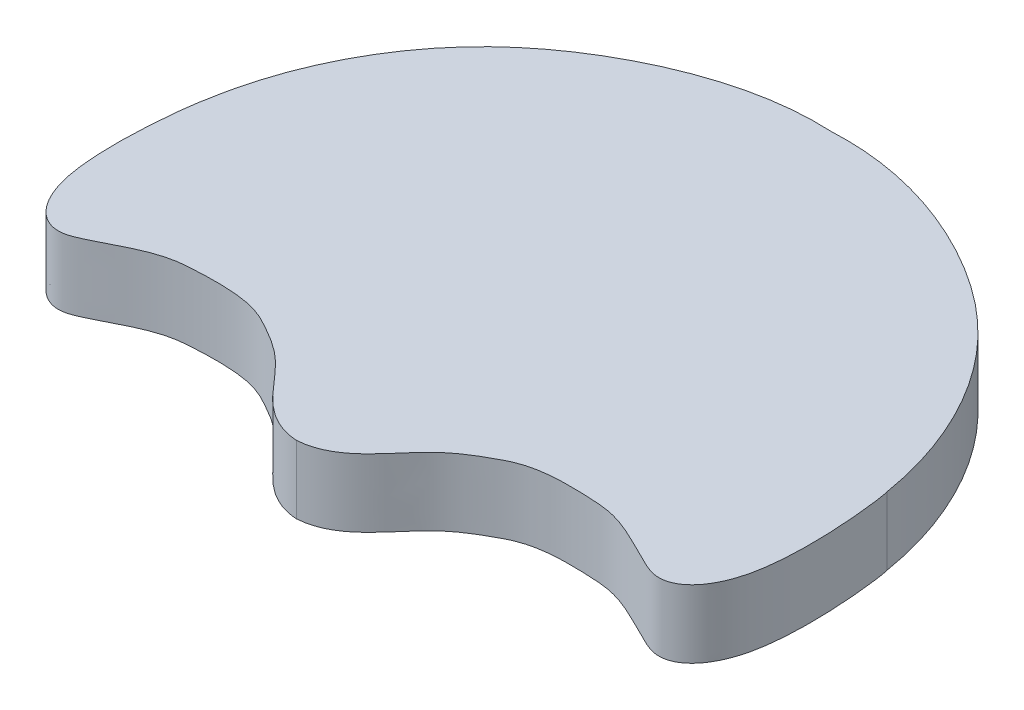
SolidWorks part; units mm, degrees
material "6061-T6 (SS)"
ref_plane "Front Plane" through (0, 0, 0) normal (0, 0, 1) x (1, 0, 0)
ref_plane "Top Plane" through (0, 0, 0) normal (0, 1, 0) x (1, 0, 0)
ref_plane "Right Plane" through (0, 0, 0) normal (1, 0, 0) x (0, 0, -1)
sketch "Sketch3" plane through (0, 0, 0) normal (0, 1, 0) x (1, 0, 0)
  line L0 (0, 0) -> (0, 159.1899) construction
  line L1 (0, 0) -> (0, -140.5301) construction
  line L2 (0, 0) -> (-190.5, 0) construction
  line L3 (0, 0) -> (190.5, 0) construction
  spline S0 degree 3 poles (-190.5, 0) (-184.3927, 37.537) (-157.2613, 93.9641) (-82.3875, 146.6227) (-31.3114, 160.7999) (0, 159.1899) knots 0 0 0 0 0.424401 0.65637 1 1 1 1
  spline S1 degree 3 poles (-190.5, 0) (-192.064, -4.9635) (-201.9672, -83.3146) (-174.6966, -109.29) (-151.6301, -100.568) (-131.4108, -87.7198) (-96.8436, -85.3754) (-78.6925, -86.2588) (-58.8335, -96.8794) (-37.3059, -109.9358) (-21.3496, -139.1148) (0, -140.5301) knots 0 0 0 0 0.166997 0.292321 0.319633 0.426735 0.458914 0.609242 0.64191 0.766802 1 1 1 1
  spline S2 degree 3 poles (190.5, 0) (192.064, -4.9635) (201.9672, -83.3146) (174.6966, -109.29) (151.6301, -100.568) (131.4108, -87.7198) (96.8436, -85.3754) (78.6925, -86.2588) (58.8335, -96.8794) (37.3059, -109.9358) (21.3496, -139.1148) (0, -140.5301) knots 0 0 0 0 0.166997 0.292321 0.319633 0.426735 0.458914 0.609242 0.64191 0.766802 1 1 1 1
  spline S3 degree 3 poles (190.5, 0) (184.3927, 37.537) (157.2613, 93.9641) (82.3875, 146.6227) (31.3114, 160.7999) (0, 159.1899) knots 0 0 0 0 0.424401 0.65637 1 1 1 1
  dimension "D1" = 381
  dimension "D2" = 299.72
  dimension "D3" = 159.1899
  dimension "D4" = 86.8953
  dimension "D5" = 104.4979
  dimension "D6" = 29.1616
  dimension "D7" = 92.2742
  dimension "D8" = 108.411
  dimension "D9" = 67.4883
  dimension "D10" = 43.7314
  dimension "D11" = 117.6915
  dimension "D12" = 162.2568
  dimension "D13" = 89.4522
  dimension "D14" = 140.1036
  dimension "D15" = 175.0666
  dimension "D16" = 50.2669
  dimension "D17" = 101.3666
  dimension "D18" = 138.1225
  dimension "D19" = 155.1557
  dimension "D20" = 192.0074
  dimension "D21" = 193.9268
  dimension "D23" = 76.6666
extrude "Boss-Extrude1" add sketch "Sketch3" along normal blind 38.1 from surface at 0 starting at plane "Top Plane"
sketch "Sketch5" plane through (0, 0, 0) normal (0, -1, 0) x (1, 0, 0)
  line L0 (0, 0) -> (0, -20.32) construction
  line L1 (31.75, -52.07) -> (-31.75, -52.07)
  line L2 (31.75, -52.07) -> (31.75, 11.43)
  line L3 (31.75, 11.43) -> (-31.75, 11.43)
  line L4 (-31.75, -52.07) -> (-31.75, 11.43)
  line L5 (31.75, -52.07) -> (-31.75, 11.43) construction
  line L6 (31.75, 11.43) -> (-31.75, -52.07) construction
  line L7 (-31.75, -52.07) -> (-31.75, -30.48)
  line L8 (-31.75, -30.48) -> (31.75, -30.48) construction
  line L9 (0, -20.32) -> (140.7253, -20.32) construction
  line L10 (0, -20.32) -> (0, -97.1287) construction
  line L11 (0, -20.32) -> (31.9753, -118.7297) construction
  line L13 (0, -20.32) -> (63.8443, -108.1942) construction
  line L14 (0, -20.32) -> (95.5392, -89.7333) construction
  line L15 (124.7166, -60.8429) -> (0, -20.32) construction
  line L16 (0, -20.32) -> (154.5508, 21.0918) construction
  line L17 (0, -20.32) -> (148.922, 65.6601) construction
  line L18 (0, -20.32) -> (-31.9753, -118.7297) construction
  line L19 (0, -20.32) -> (-63.8443, -108.1942) construction
  line L20 (0, -20.32) -> (-95.5392, -89.7333) construction
  line L21 (-124.7166, -60.8429) -> (0, -20.32) construction
  line L22 (0, -20.32) -> (-154.5508, 21.0918) construction
  line L23 (0, -20.32) -> (-148.922, 65.6601) construction
  spline S0 degree 3 poles (-148.922, 65.6601) (-157.8584, 40.2253) (-156.2837, 8.5854) (-143.1202, -28.9506) (-139.3242, -37.3463) (-130.3709, -53.1962) (-125.215, -60.649) (-118.0488, -69.1403) (-116.5795, -70.7975) (-113.5719, -74.0252) (-112.0368, -75.592) (-107.2801, -80.2116) (-103.9215, -83.1695) (-93.3361, -91.6595) (-85.5959, -96.8074) (-76.3408, -101.9556) (-75.3049, -102.5187) (-73.219, -103.6268) (-72.1677, -104.1726) (-69.0049, -105.7765) (-66.8862, -106.8006) (-60.5068, -109.7299) (-56.2231, -111.4921) (-47.6308, -114.6027) (-43.3223, -115.9511) (-34.7104, -118.209) (-30.4072, -119.1185) (-21.8242, -120.4791) (-17.5446, -120.9304) (-11.1443, -121.2499) (-9.0138, -121.2968) (-5.8216, -121.2757) (-4.1848, -121.2414) (-2.5489, -121.1705) (-1.9677, -121.1408) (-1.9605, -121.1404) (-1.2995, -121.1064) (-0.6497, -121.073) (0, -121.0396) knots -0.292878 -0.292878 -0.292878 -0.292878 0.125 0.125 0.25 0.25 0.375 0.375 0.40625 0.40625 0.4375 0.4375 0.5 0.5 0.625 0.625 0.640625 0.640625 0.65625 0.65625 0.6875 0.6875 0.75 0.75 0.8125 0.8125 0.875 0.875 0.9375 0.9375 0.96875 0.96875 0.984375 0.992798 0.992798 0.99292 0.99292 1 1 1 1
  spline S5 degree 3 poles (998.6789, -69.6893) (665.1581, -86.8384) (331.6156, -103.9885) (-1.9268, -121.1387) (-1.9605, -121.1404) (-1.9677, -121.1408) (-2.5489, -121.1705) (-4.1848, -121.2414) (-5.8216, -121.2757) (-9.0138, -121.2968) (-11.1443, -121.2499) (-17.5446, -120.9304) (-21.8242, -120.4791) (-30.4072, -119.1185) (-34.7104, -118.209) (-43.3223, -115.9511) (-47.6308, -114.6027) (-56.2231, -111.4921) (-60.5068, -109.7299) (-66.8862, -106.8006) (-69.0049, -105.7765) (-72.1677, -104.1726) (-73.219, -103.6268) (-75.3049, -102.5187) (-76.3408, -101.9556) (-85.5959, -96.8074) (-93.3361, -91.6595) (-103.9215, -83.1695) (-107.2801, -80.2116) (-112.0368, -75.592) (-113.5719, -74.0252) (-116.5795, -70.7975) (-118.0488, -69.1403) (-125.215, -60.649) (-130.3709, -53.1962) (-139.3242, -37.3463) (-143.1202, -28.9506) (-198.5095, 128.9933) (-22.362, 351.6373) (651.8169, -587.5188) knots -3.627409 -3.627409 -3.627409 -3.627409 0.006836 0.00708 0.00708 0.007202 0.007202 0.015625 0.03125 0.03125 0.0625 0.0625 0.125 0.125 0.1875 0.1875 0.25 0.25 0.3125 0.3125 0.34375 0.34375 0.359375 0.359375 0.375 0.375 0.5 0.5 0.5625 0.5625 0.59375 0.59375 0.625 0.625 0.75 0.75 0.875 0.875 3.034324 3.034324 3.034324 3.034324 only from (0, -121.0396) to (-152.8945, 6.1184)
  spline S6 degree 3 poles (-1687.8289, -2297.0686) (-150.4269, 537.0593) (218.9922, 187.4002) (143.1202, -28.9506) (139.3242, -37.3463) (130.3709, -53.1962) (125.215, -60.649) (118.0488, -69.1403) (116.5795, -70.7975) (113.5719, -74.0252) (112.0368, -75.592) (107.2801, -80.2116) (103.9215, -83.1695) (93.3361, -91.6595) (85.5959, -96.8074) (76.3408, -101.9556) (75.3049, -102.5187) (73.219, -103.6268) (72.1677, -104.1726) (69.0049, -105.7765) (66.8862, -106.8006) (60.5068, -109.7299) (56.2231, -111.4921) (47.6308, -114.6027) (43.3223, -115.9511) (34.7104, -118.209) (30.4072, -119.1185) (21.8242, -120.4791) (17.5446, -120.9304) (11.1443, -121.2499) (9.0138, -121.2968) (5.8216, -121.2757) (4.1848, -121.2414) (2.5489, -121.1705) (1.9677, -121.1408) (1.9605, -121.1404) (-997.3522, -69.7575) (-1996.6535, -18.3753) (-2996.029, 33.0152) knots -2.879056 -2.879056 -2.879056 -2.879056 0.125 0.125 0.25 0.25 0.375 0.375 0.40625 0.40625 0.4375 0.4375 0.5 0.5 0.625 0.625 0.640625 0.640625 0.65625 0.65625 0.6875 0.6875 0.75 0.75 0.8125 0.8125 0.875 0.875 0.9375 0.9375 0.96875 0.96875 0.984375 0.992798 0.992798 0.99292 0.99292 11.881939 11.881939 11.881939 11.881939 only from (152.8945, 6.1184) to (0, -121.0396)
  spline S8 degree 3 poles (148.922, 65.6601) (157.8584, 40.2253) (156.2837, 8.5854) (143.1202, -28.9506) (139.3242, -37.3463) (130.3709, -53.1962) (125.215, -60.649) (118.0488, -69.1403) (116.5795, -70.7975) (113.5719, -74.0252) (112.0368, -75.592) (107.2801, -80.2116) (103.9215, -83.1695) (93.3361, -91.6595) (85.5959, -96.8074) (76.3408, -101.9556) (75.3049, -102.5187) (73.219, -103.6268) (72.1677, -104.1726) (69.0049, -105.7765) (66.8862, -106.8006) (60.5068, -109.7299) (56.2231, -111.4921) (47.6308, -114.6027) (43.3223, -115.9511) (34.7104, -118.209) (30.4072, -119.1185) (21.8242, -120.4791) (17.5446, -120.9304) (11.1443, -121.2499) (9.0138, -121.2968) (5.8216, -121.2757) (4.1848, -121.2414) (2.5489, -121.1705) (1.9677, -121.1408) (1.9605, -121.1404) (1.2995, -121.1064) (0.6497, -121.073) (0, -121.0396) knots -0.292878 -0.292878 -0.292878 -0.292878 0.125 0.125 0.25 0.25 0.375 0.375 0.40625 0.40625 0.4375 0.4375 0.5 0.5 0.625 0.625 0.640625 0.640625 0.65625 0.65625 0.6875 0.6875 0.75 0.75 0.8125 0.8125 0.875 0.875 0.9375 0.9375 0.96875 0.96875 0.984375 0.992798 0.992798 0.99292 0.99292 1 1 1 1
  point P0 (0, -20.32)
  point P3 (0, -20.32)
  point P14 (0, 114.3)
  point P16 (0, 88.9)
  dimension "D1" = 20.32
  dimension "D2" = 63.5
  dimension "D3" = 63.5
  dimension "D4" = 21.59
  dimension "D6" = 25.4
  dimension "D7" = 88.9
  dimension "D8" = 18
  dimension "D9" = 18
  dimension "D10" = 18
  dimension "D11" = 18
  dimension "D12" = 15
  dimension "D13" = 15
  dimension "D5" = 38.1
equation "\"Plate thickness\"=1.5"
equation "\"D1@Boss-Extrude1\"=\"Plate thickness\""
equation "\"Bracket Alignment\"= .80"
equation "\"D1@Sketch5\"=\"Bracket Alignment\""
